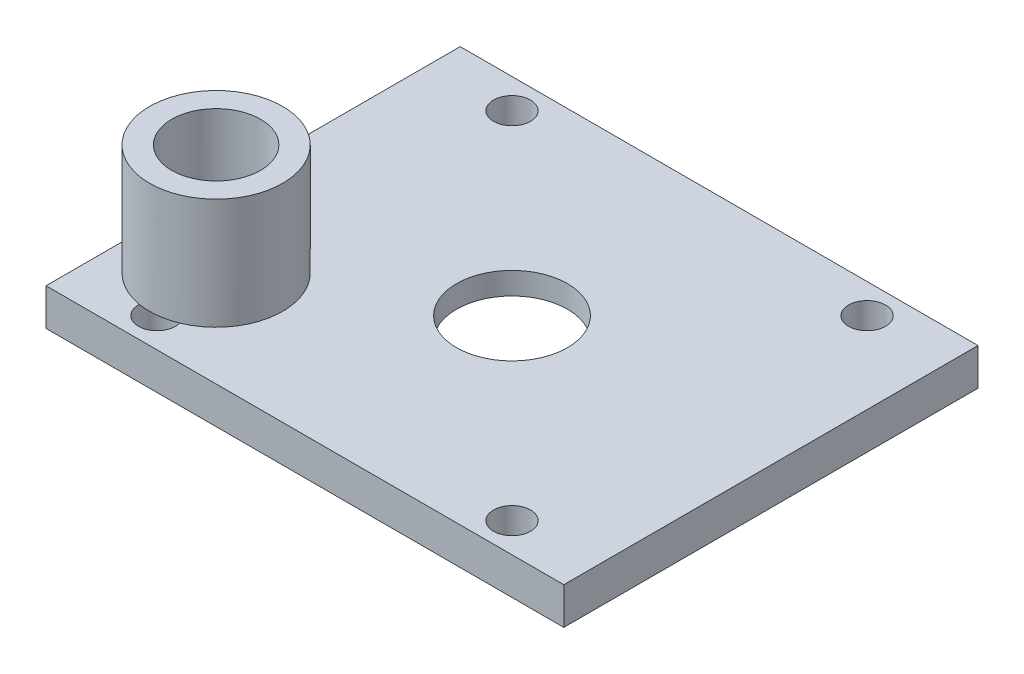
SolidWorks part; units mm, degrees
ref_plane "Front Plane" through (0, 0, 0) normal (0, 0, 1) x (1, 0, 0)
ref_plane "Top Plane" through (0, 0, 0) normal (0, 1, 0) x (1, 0, 0)
ref_plane "Right Plane" through (0, 0, 0) normal (1, 0, 0) x (0, 0, -1)
sketch "Sketch1" plane through (0, 0, 0) normal (0, 1, 0) x (1, 0, 0)
  line L1 (-35, -28) -> (35, -28)
  line L2 (-35, -28) -> (-35, 28)
  line L3 (-35, 28) -> (35, 28)
  line L4 (35, -28) -> (35, 28)
  line L5 (-35, -28) -> (35, 28) construction
  line L6 (-35, 28) -> (35, -28) construction
  point P0 (0, 0)
  dimension "D1" = 70
  dimension "D2" = 56
extrude "Boss-Extrude1" add sketch "Sketch1" along normal blind 5
sketch "Sketch2" plane through (0, 5, 0) normal (0, 1, 0) x (1, 0, 0)
  circle A0 centre (-25, -15) radius 9
  point P2 (0, 0)
  dimension "D1" = 18
  dimension "D2" = 15
  dimension "D3" = 25
extrude "Boss-Extrude2" add sketch "Sketch2" along normal blind 15
sketch "Sketch4" plane through (0, 0, 0) normal (0, -1, 0) x (1, 0, 0)
  circle A0 centre (0, 0) radius 19
  dimension "D1" = 38
extrude "Cut-Extrude2" cut sketch "Sketch4" against normal blind 2
sketch "Sketch5" plane through (0, 2, 0) normal (0, -1, 0) x (1, 0, 0)
  circle A0 centre (0, 0) radius 7.5
  dimension "D1" = 15
extrude "Cut-Extrude3" cut sketch "Sketch5" against normal through all and the other way through all
sketch "Sketch6" plane through (0, 20, 0) normal (0, 1, 0) x (1, 0, 0)
  circle A0 centre (-25, -15) radius 6
  dimension "D1" = 12
extrude "Cut-Extrude4" cut sketch "Sketch6" along direction (0, -1, 0) on the side against the normal up to surface (15 mm away)
sketch "Sketch7" plane through (0, 5, 0) normal (0, 1, 0) x (1, 0, 0)
  circle A0 centre (-24, 24) radius 2.5
  circle A1 centre (24, 24) radius 2.5
  circle A2 centre (24, -24) radius 2.5
  circle A3 centre (-24, -24) radius 2.5
  point P2 (0, 0)
  point P13 (0, 0)
  dimension "D1" = 24
  dimension "D2" = 5
  dimension "D3" = 24
  dimension "D4" = 4
extrude "Cut-Extrude5" cut sketch "Sketch7" against normal through all
